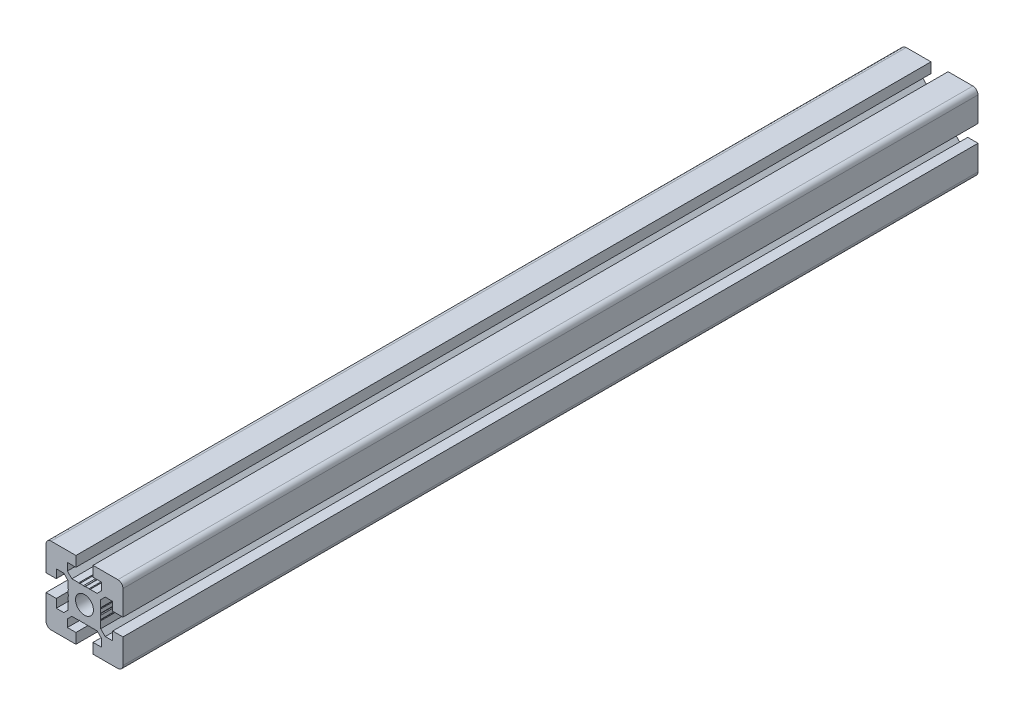
SolidWorks part; units mm, degrees
ref_plane "Front Plane" through (0, 0, 0) normal (0, 0, 1) x (1, 0, 0)
ref_plane "Top Plane" through (0, 0, 0) normal (0, 1, 0) x (1, 0, 0)
ref_plane "Right Plane" through (0, 0, 0) normal (1, 0, 0) x (0, 0, -1)
ref_plane "Plane1" through (0, 0, -200) normal (0, 0, -1) x (-1, 0, 0)
sketch "Sketch1" plane through (0, 0, -200) normal (0, 0, -1) x (-1, 0, 0)
  line L0 (19.5, 22.5) -> (5, 22.5)
  line L1 (5, 22.5) -> (5, 16.5)
  line L2 (5, 16.5) -> (10, 16.5)
  line L3 (10, 16.5) -> (10, 12.1213)
  line L4 (10, 12.1213) -> (7.3787, 9.5)
  line L5 (7.3787, 9.5) -> (3.3464, 9.5)
  line L6 (3.3464, 9.5) -> (3, 9.3)
  line L7 (3, 9.3) -> (2.6536, 9.5)
  line L8 (2.6536, 9.5) -> (0.5196, 9.5)
  line L9 (0.5196, 9.5) -> (0, 9.2)
  line L10 (0, 9.2) -> (-0.5196, 9.5)
  line L11 (-0.5196, 9.5) -> (-2.6536, 9.5)
  line L12 (-2.6536, 9.5) -> (-3, 9.3)
  line L13 (-3, 9.3) -> (-3.3464, 9.5)
  line L14 (-3.3464, 9.5) -> (-7.3787, 9.5)
  line L15 (-7.3787, 9.5) -> (-10, 12.1213)
  line L16 (-10, 12.1213) -> (-10, 16.5)
  line L17 (-10, 16.5) -> (-5, 16.5)
  line L18 (-5, 16.5) -> (-5, 22.5)
  line L19 (-5, 22.5) -> (-19.5, 22.5)
  line L20 (-22.5, 19.5) -> (-22.5, 5)
  line L21 (-22.5, 5) -> (-16.5, 5)
  line L22 (-16.5, 5) -> (-16.5, 10)
  line L23 (-16.5, 10) -> (-12.1213, 10)
  line L24 (-12.1213, 10) -> (-9.5, 7.3787)
  line L25 (-9.5, 7.3787) -> (-9.5, 3.3464)
  line L26 (-9.5, 3.3464) -> (-9.3, 3)
  line L27 (-9.3, 3) -> (-9.5, 2.6536)
  line L28 (-9.5, 2.6536) -> (-9.5, 0.5196)
  line L29 (-9.5, 0.5196) -> (-9.2, 0)
  line L30 (-9.2, 0) -> (-9.5, -0.5196)
  line L31 (-9.5, -0.5196) -> (-9.5, -2.6536)
  line L32 (-9.5, -2.6536) -> (-9.3, -3)
  line L33 (-9.3, -3) -> (-9.5, -3.3464)
  line L34 (-9.5, -3.3464) -> (-9.5, -7.3787)
  line L35 (-9.5, -7.3787) -> (-12.1213, -10)
  line L36 (-12.1213, -10) -> (-16.5, -10)
  line L37 (-16.5, -10) -> (-16.5, -5)
  line L38 (-16.5, -5) -> (-22.5, -5)
  line L39 (-22.5, -5) -> (-22.5, -19.5)
  line L40 (-19.5, -22.5) -> (-5, -22.5)
  line L41 (-5, -22.5) -> (-5, -16.5)
  line L42 (-5, -16.5) -> (-10, -16.5)
  line L43 (-10, -16.5) -> (-10, -12.1213)
  line L44 (-10, -12.1213) -> (-7.3787, -9.5)
  line L45 (-7.3787, -9.5) -> (-3.3464, -9.5)
  line L46 (-3.3464, -9.5) -> (-3, -9.3)
  line L47 (-3, -9.3) -> (-2.6536, -9.5)
  line L48 (-2.6536, -9.5) -> (-0.5196, -9.5)
  line L49 (-0.5196, -9.5) -> (0, -9.2)
  line L50 (0, -9.2) -> (0.5196, -9.5)
  line L51 (0.5196, -9.5) -> (2.6536, -9.5)
  line L52 (2.6536, -9.5) -> (3, -9.3)
  line L53 (3, -9.3) -> (3.3464, -9.5)
  line L54 (3.3464, -9.5) -> (7.3787, -9.5)
  line L55 (7.3787, -9.5) -> (10, -12.1213)
  line L56 (10, -12.1213) -> (10, -16.5)
  line L57 (10, -16.5) -> (5, -16.5)
  line L58 (5, -16.5) -> (5, -22.5)
  line L59 (5, -22.5) -> (19.5, -22.5)
  line L60 (22.5, -19.5) -> (22.5, -5)
  line L61 (22.5, -5) -> (16.5, -5)
  line L62 (16.5, -5) -> (16.5, -10)
  line L63 (16.5, -10) -> (12.1213, -10)
  line L64 (12.1213, -10) -> (9.5, -7.3787)
  line L65 (9.5, -7.3787) -> (9.5, -3.3464)
  line L66 (9.5, -3.3464) -> (9.3, -3)
  line L67 (9.3, -3) -> (9.5, -2.6536)
  line L68 (9.5, -2.6536) -> (9.5, -0.5196)
  line L69 (9.5, -0.5196) -> (9.2, 0)
  line L70 (9.2, 0) -> (9.5, 0.5196)
  line L71 (9.5, 0.5196) -> (9.5, 2.6536)
  line L72 (9.5, 2.6536) -> (9.3, 3)
  line L73 (9.3, 3) -> (9.5, 3.3464)
  line L74 (9.5, 3.3464) -> (9.5, 7.3787)
  line L75 (9.5, 7.3787) -> (12.1213, 10)
  line L76 (12.1213, 10) -> (16.5, 10)
  line L77 (16.5, 10) -> (16.5, 5)
  line L78 (16.5, 5) -> (22.5, 5)
  line L79 (22.5, 5) -> (22.5, 19.5)
  circle A0 centre (0, 0) radius 5.25
  arc A1 (22.5, 19.5) -> (19.5, 22.5) centre (19.5, 19.5) ccw
  arc A2 (-19.5, 22.5) -> (-22.5, 19.5) centre (-19.5, 19.5) ccw
  arc A3 (-22.5, -19.5) -> (-19.5, -22.5) centre (-19.5, -19.5) ccw
  arc A4 (19.5, -22.5) -> (22.5, -19.5) centre (19.5, -19.5) ccw
extrude "Boss-Extrude1" add sketch "Sketch1" against normal blind 500
